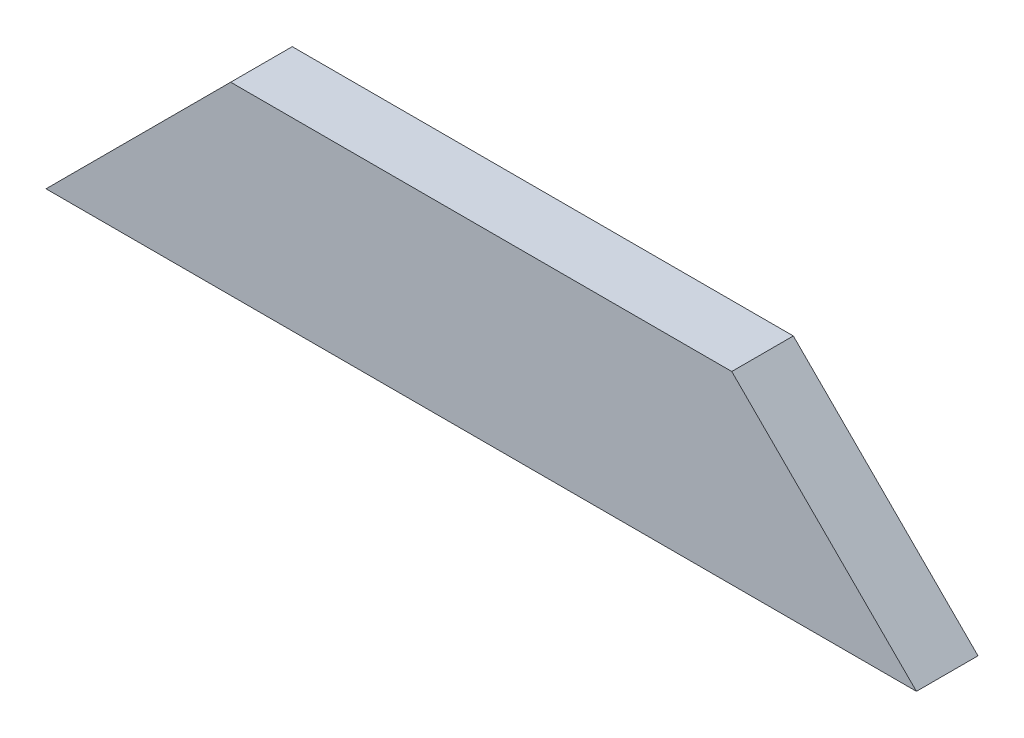
SolidWorks part; units mm, degrees
ref_plane "Front Plane" through (0, 0, 0) normal (0, 0, 1) x (1, 0, 0)
ref_plane "Top Plane" through (0, 0, 0) normal (0, 1, 0) x (1, 0, 0)
ref_plane "Right Plane" through (0, 0, 0) normal (1, 0, 0) x (0, 0, -1)
sketch "Sketch2" plane through (0, 0, 0) normal (0, 0, 1) x (1, 0, 0)
  line L0 (-353.5, -75) -> (-203.5, 75)
  line L1 (-203.5, 75) -> (203.5, 75)
  line L3 (-353.5, -75) -> (353.5, -75)
  line L5 (-353.5, 75) -> (353.5, -75) construction
  line L6 (-353.5, -75) -> (353.5, 75) construction
  line L7 (203.5, 75) -> (353.5, -75)
  point P0 (0, 0)
  dimension "D1" = 135
  dimension "D2" = 707
  dimension "D3" = 150
  dimension "D4" = 135
extrude "Boss-Extrude3" add sketch "Sketch2" along normal mid plane 50
